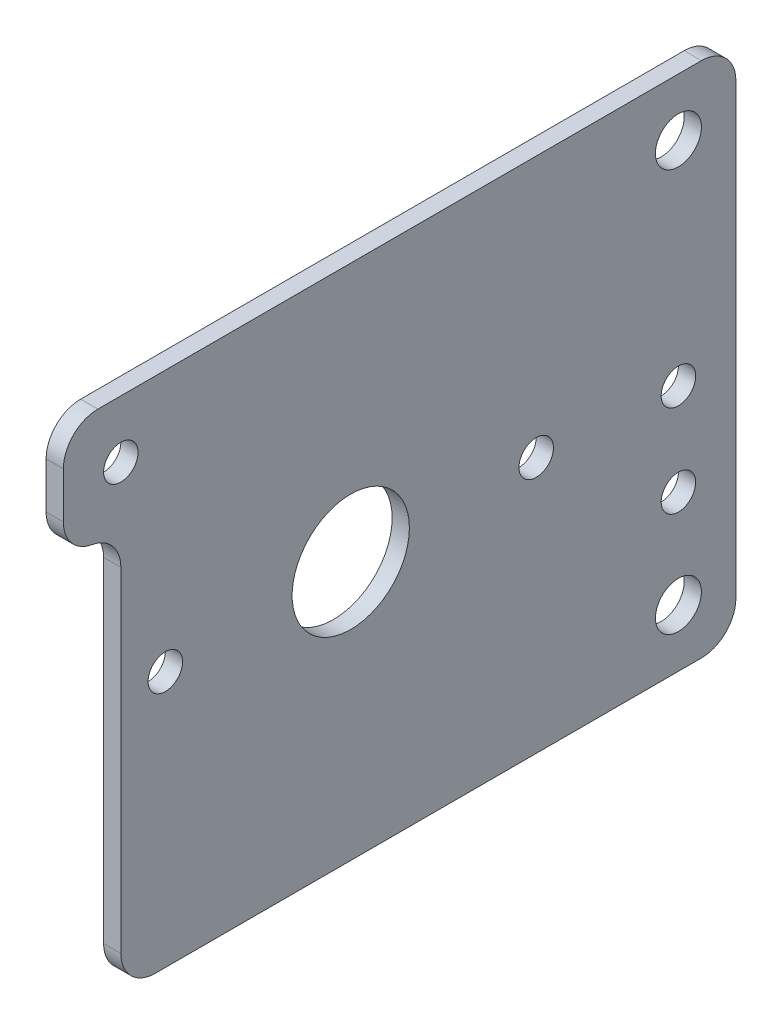
SolidWorks part; units mm, degrees
material "1060 合金"
ref_plane "正面" through (0, 0, 0) normal (0, 0, 1) x (1, 0, 0)
ref_plane "平面" through (0, 0, 0) normal (0, 1, 0) x (1, 0, 0)
ref_plane "右側面" through (0, 0, 0) normal (1, 0, 0) x (0, 0, -1)
sketch "ｽｹｯﾁ1" plane through (0, 0, 0) normal (1, 0, 0) x (0, 0, -1)
  line L0 (-26.75, 0) -> (26.75, 0) construction
  line L1 (-26.75, -22.5) -> (26.75, -22.5)
  line L2 (-26.75, -22.5) -> (-26.75, 22.5)
  line L3 (-26.75, 22.5) -> (26.75, 22.5)
  line L4 (26.75, -22.5) -> (26.75, 22.5)
  line L5 (-26.75, -22.5) -> (26.75, 22.5) construction
  line L6 (-26.75, 22.5) -> (26.75, -22.5) construction
  line L7 (-6.75, 13) -> (-6.75, -13) construction
  line L8 (-6.75, 0) -> (-6.75, 14.3689) construction
  line L9 (-6.75, 0) -> (-22.88, 0) construction
  line L10 (-22.88, 0.21) -> (-22.88, 0) construction
  line L11 (21.75, 17.5) -> (21.75, 0) construction
  line L12 (-6.75, 0) -> (9.38, 0) construction
  line L13 (9.38, 0) -> (9.38, 0.21) construction
  line L14 (21.75, 0) -> (21.75, -22.5) construction
  circle A0 centre (-6.75, 0) radius 5.1
  circle A6 centre (21.75, 17.5) radius 2
  circle A12 centre (9.38, 0) radius 1.5 construction
  circle A13 centre (-22.88, 0) radius 1.5 construction
  circle A14 centre (9.38, 0.21) radius 1.5 construction
  circle A15 centre (-22.88, 0.21) radius 1.5 construction
  circle A16 centre (21.75, 0) radius 2 construction
  circle A17 centre (-22.88, -0.21) radius 1.5
  circle A18 centre (9.38, -0.21) radius 1.5
  circle A19 centre (21.75, -1) radius 1.5
  circle A21 centre (21.75, -17.5) radius 2
  circle A22 centre (21.75, -9) radius 1.5
  point P0 (0, 0)
  dimension "D1" = 10.2
  dimension "D2" = 20
  dimension "D4" = 17.5
  dimension "D6" = 23.5
  dimension "D7" = 5
  dimension "D8" = 5
  dimension "D9" = 4
  dimension "D11" = 3
  dimension "D12" = 8
  dimension "D14" = 32.26
  dimension "D16" = 3
  dimension "D3" = 0.21
  dimension "D5" = 16.13
  dimension "D10" = 53.5
  dimension "D15" = 0.21
extrude "ﾎﾞｽ - 押し出し1" add sketch "ｽｹｯﾁ1" along normal blind 1.5
sketch "ｽｹｯﾁ3" plane through (1.5, 0, 0) normal (1, 0, 0) x (0, 0, -1)
  line L1 (-31.75, 12.5) -> (-26.75, 12.5)
  line L2 (-31.75, 12.5) -> (-31.75, 22.5)
  line L3 (-31.75, 22.5) -> (-26.75, 22.5)
  line L4 (-26.75, 12.5) -> (-26.75, 22.5)
  line L5 (-31.75, 12.5) -> (-26.75, 22.5) construction
  line L6 (-31.75, 22.5) -> (-26.75, 12.5) construction
  point P0 (-29.25, 17.5)
  dimension "D1" = 5
  dimension "D2" = 10
extrude "ﾎﾞｽ - 押し出し2" add sketch "ｽｹｯﾁ3" against normal up to surface (1.5 mm away) up to face at (0, -1, -23.25)
sketch "ｽｹｯﾁ4" plane through (1.5, 0, 0) normal (1, 0, 0) x (0, 0, -1)
  line L0 (-41.75, 17.5) -> (49958.25, 17.5) construction
  line L1 (-31.75, 22.5) -> (-31.75, 12.5) construction
  line L2 (21.75, -17.5) -> (21.75, 49982.5) construction
  line L4 (26.75, -22.5) -> (26.75, 22.5) construction
  line L5 (0, 0) -> (50000, 0) construction
  circle A0 centre (-26.75, 17.5) radius 1.5
  point P4 (-31.75, 17.5)
  dimension "D1" = 5
  dimension "D2" = 3
  dimension "D5" = 5
extrude "ｶｯﾄ - 押し出し2" cut sketch "ｽｹｯﾁ4" against normal through all
fillet "ﾌｨﾚｯﾄ1" radius 3 5 edges at (0.75, -22.5, -26.75) (0.75, 22.5, -26.75) (0.75, -22.5, 26.75) (0.75, 12.5, 31.75) (0.75, 22.5, 31.75)
fillet "ﾌｨﾚｯﾄ2" radius 3 1 edges at (0.75, 12.5, 26.75)
equation "\"s\"=3"
